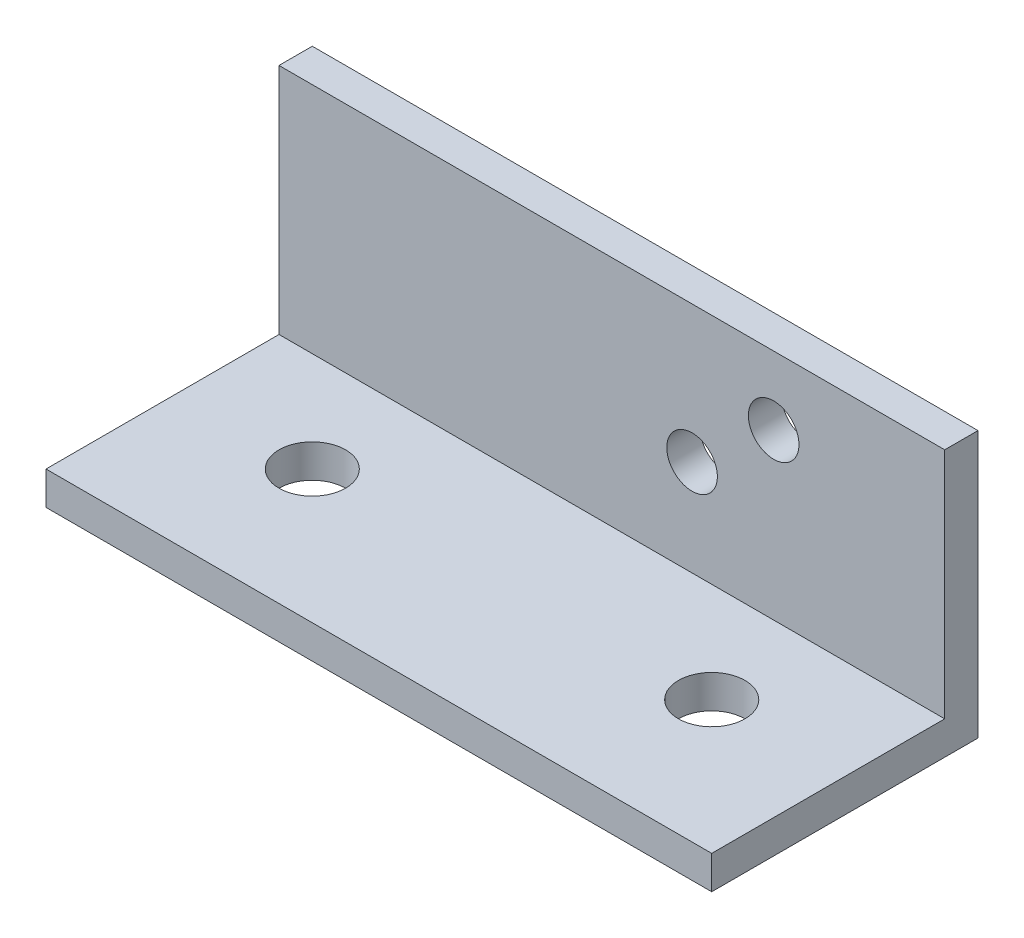
SolidWorks part; units mm, degrees
material "6061-T6 (SS)"
ref_plane "Front Plane" through (0, 0, 0) normal (0, 0, 1) x (1, 0, 0)
ref_plane "Top Plane" through (0, 0, 0) normal (0, 1, 0) x (1, 0, 0)
ref_plane "Right Plane" through (0, 0, 0) normal (1, 0, 0) x (0, 0, -1)
sketch "Sketch1" plane through (0, 0, 0) normal (0, 1, 0) x (1, 0, 0)
  line L1 (0, 0) -> (63.5, 0)
  line L2 (0, 0) -> (0, -25.4)
  line L3 (0, -25.4) -> (63.5, -25.4)
  line L4 (63.5, 0) -> (63.5, -25.4)
  dimension "D1" = 25.4
  dimension "D2" = 63.5
extrude "Boss-Extrude1" add sketch "Sketch1" along normal blind 3.175
sketch "Sketch2" plane through (0, 3.175, 0) normal (0, 1, 0) x (1, 0, 0)
  line L0 (63.5, -25.4) -> (63.5, 0) construction
  line L1 (0, 0) -> (63.5, 0)
  line L2 (0, 0) -> (0, -3.175)
  line L3 (0, -3.175) -> (63.5, -3.175)
  line L4 (63.5, 0) -> (63.5, -3.175)
  dimension "D1" = 3.175
extrude "Boss-Extrude2" add sketch "Sketch2" along normal blind 22.225
sketch "Sketch3" plane through (0, 3.175, 0) normal (0, 1, 0) x (1, 0, 0)
  line L1 (63.5, -25.4) -> (50.8, -25.4) construction
  line L2 (63.5, -25.4) -> (63.5, -12.7) construction
  line L3 (63.5, -12.7) -> (50.8, -12.7) construction
  line L4 (50.8, -25.4) -> (50.8, -12.7) construction
  line L5 (0, -25.4) -> (12.7, -25.4)
  line L6 (0, -25.4) -> (0, -12.7)
  line L7 (0, -12.7) -> (12.7, -12.7) construction
  line L8 (12.7, -25.4) -> (12.7, -12.7) construction
  circle A0 centre (12.7, -12.7) radius 3.175
  circle A1 centre (50.8, -12.7) radius 3.175
  dimension "D5" = 6.35
  dimension "D6" = 6.35
  dimension "D1" = 12.7
  dimension "D2" = 12.7
  dimension "D3" = 12.7
  dimension "D4" = 12.7
extrude "Cut-Extrude1" cut sketch "Sketch3" against normal blind 3.175 contours L3 A1 L4 | L4 A1 L3 | A0
sketch "Sketch4" plane through (0, 0, 0) normal (0, 0, -1) x (-1, 0, 0)
  line L0 (-79.6648, 25.4) -> (-49.3942, 0) construction
  line L1 (-63.5, 0) -> (0, 0) construction
  line L2 (0, 25.4) -> (0, 0) construction
  line L3 (0, 0) -> (-30.2705, 25.4) construction
  line L4 (-63.5, 25.4) -> (0, 25.4) construction
  line L5 (-30.2705, 25.4) -> (-63.5, 25.4) construction
  line L6 (-33.2295, 0) -> (0, 0) construction
  line L7 (-79.6648, 25.4) -> (-30.2705, 25.4) construction
  line L8 (-54.9677, 25.4) -> (-24.6971, 0) construction
  circle A0 centre (-47.1846, 18.8693) radius 2.413
  circle A1 centre (-39.4016, 12.3386) radius 2.413
  dimension "D2" = 50
  dimension "D3" = 4.826
  dimension "D4" = 4.826
  dimension "D5" = 10.16
  dimension "D6" = 10.16
  dimension "D1" = 31.75
extrude "Cut-Extrude2" cut sketch "Sketch4" against normal blind 3.175
